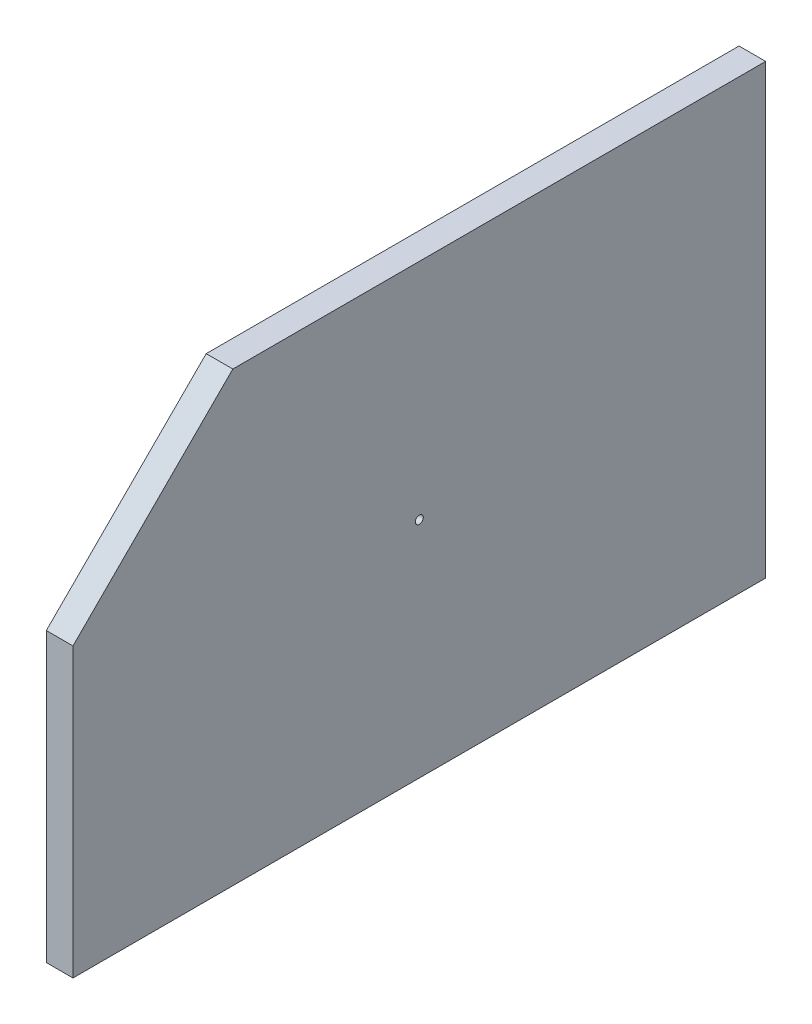
SolidWorks part; units mm, degrees
ref_plane "Ön Düzlem" through (0, 0, 0) normal (0, 0, 1) x (1, 0, 0)
ref_plane "Üst Düzlem" through (0, 0, 0) normal (0, 1, 0) x (1, 0, 0)
ref_plane "Sağ Düzlem" through (0, 0, 0) normal (1, 0, 0) x (0, 0, -1)
sketch "Çizim1" plane through (0, 0, 0) normal (1, 0, 0) x (0, 0, -1)
  line L0 (0, 0) -> (260, 0)
  line L1 (260, 0) -> (260, 167.95)
  line L2 (260, 167.95) -> (60, 167.95)
  line L3 (60, 167.95) -> (0, 107.95)
  line L4 (0, 107.95) -> (0, 0)
  dimension "D1" = 200
  dimension "D2" = 167.95
  dimension "D3" = 260
  dimension "D4" = 107.95
extrude "Yükseklik-Ekstrüzyon1" add sketch "Çizim1" along normal blind 10
sketch "Sketch3" plane through (10, 0, 0) normal (1, 0, 0) x (0, 0, -1)
  circle A0 centre (130, 83.975) radius 1.5
  dimension "D1" = 3
extrude "Cut-Extrude1" cut sketch "Sketch3" against normal blind 10
